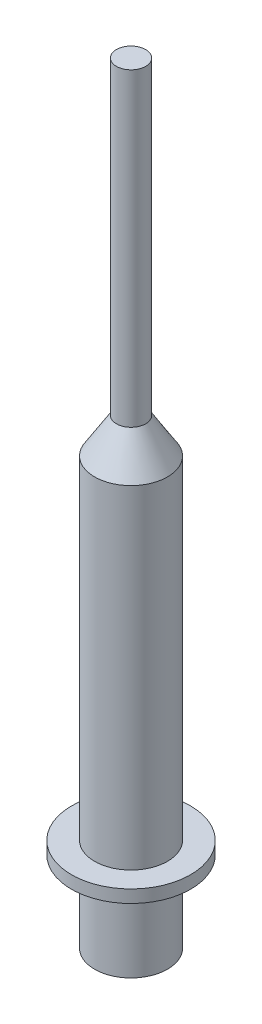
SolidWorks part; units mm, degrees
material "AISI Type 316L stainless steel"
ref_plane "Front Plane" through (0, 0, 0) normal (0, 0, 1) x (1, 0, 0)
ref_plane "Top Plane" through (0, 0, 0) normal (0, 1, 0) x (1, 0, 0)
ref_plane "Right Plane" through (0, 0, 0) normal (1, 0, 0) x (0, 0, -1)
sketch "Sketch1" plane through (0, 0, 0) normal (0, 1, 0) x (1, 0, 0)
  circle A0 centre (0, 0) radius 3.9624
  dimension "D1" = 7.9248
extrude "Boss-Extrude1" add sketch "Sketch1" along normal blind 46.355
ref_plane "Plane1" through (0, 50.165, 0) normal (0, 1, 0) x (1, 0, 0)
sketch "Sketch2" plane through (0, 50.165, 0) normal (0, 1, 0) x (1, 0, 0)
  circle A0 centre (0, 0) radius 1.5875
  dimension "D1" = 3.175
sketch "Sketch3" plane through (0, 46.355, 0) normal (0, 1, 0) x (1, 0, 0)
  circle A0 centre (0, 0) radius 3.9624
loft "Loft1" add profiles "Sketch3", "Sketch2"
sketch "Sketch4" plane through (0, 50.165, 0) normal (0, 1, 0) x (1, 0, 0)
  circle A0 centre (0, 0) radius 1.5875
extrude "Boss-Extrude2" add sketch "Sketch4" along normal blind 33.655 contours A0
ref_plane "Plane2" through (0, 10.16, 0) normal (0, -1, 0) x (-1, 0, 0)
sketch "Sketch5" plane through (0, 10.16, 0) normal (0, -1, 0) x (-1, 0, 0)
  circle A0 centre (0, 0) radius 6.477
  dimension "D1" = 12.954
extrude "Boss-Extrude3" add sketch "Sketch5" along normal blind 1.3716
